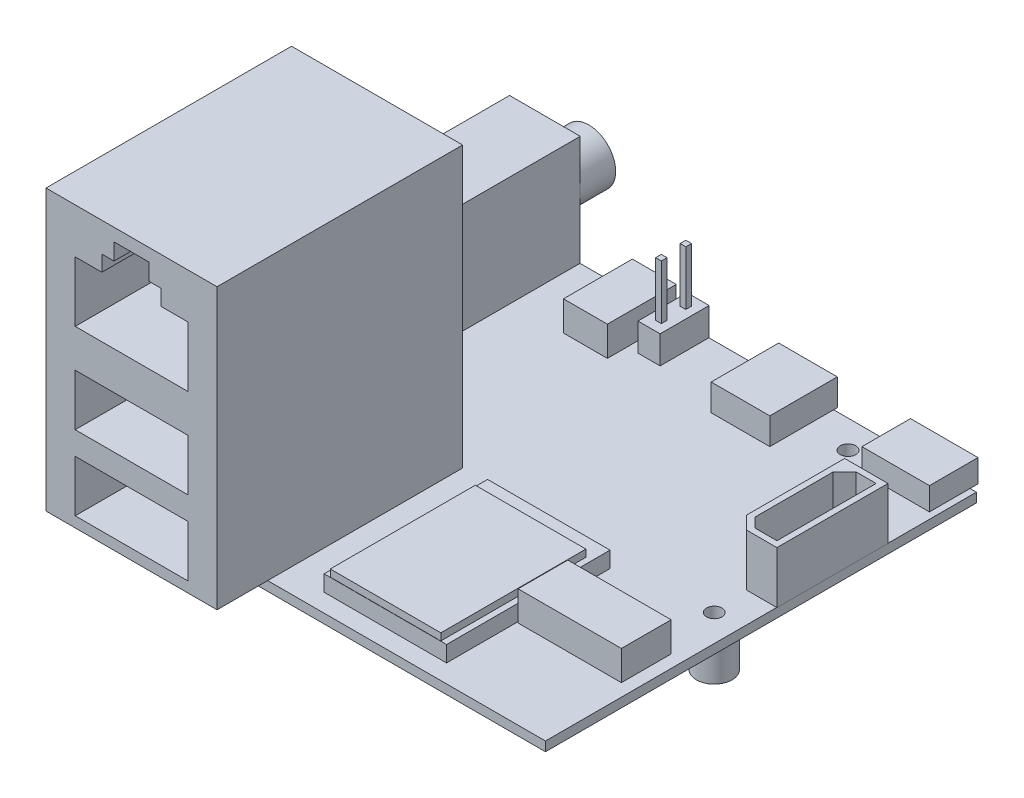
SolidWorks part; units mm, degrees
material "Delrin 2700 NC010, Low Viscosity Acetal Copolymer (SS)"
ref_plane "Front Plane" through (0, 0, 0) normal (0, 0, 1) x (1, 0, 0)
ref_plane "Top Plane" through (0, 0, 0) normal (0, 1, 0) x (1, 0, 0)
ref_plane "Right Plane" through (0, 0, 0) normal (1, 0, 0) x (0, 0, -1)
sketch "Sketch1" plane through (0, 0, 0) normal (0, 1, 0) x (1, 0, 0)
  line L1 (0, 0) -> (52, 0)
  line L2 (0, 0) -> (0, 48)
  line L3 (0, 48) -> (52, 48)
  line L4 (52, 0) -> (52, 48)
  dimension "D1" = 52
  dimension "D2" = 48
extrude "Base" add sketch "Sketch1" along normal blind 1.04
sketch "Sketch3" plane through (0, 1.04, 0) normal (0, 1, 0) x (1, 0, 0)
  line L0 (0, 0) -> (52, 0) construction
  line L1 (21.0566, 21.7112) -> (2.0066, 21.7112)
  line L2 (21.0566, 21.7112) -> (21.0566, -5.6388)
  line L3 (21.0566, -5.6388) -> (2.0066, -5.6388)
  line L4 (2.0066, 21.7112) -> (2.0066, -5.6388)
  line L5 (0, 48) -> (0, 0) construction
  dimension "D1" = 27.35
  dimension "D2" = 19.05
  dimension "D3" = 5.6388
  dimension "D4" = 2.0066
extrude "Ethernet-USB-LinkPP" add sketch "Sketch3" along normal blind 31.1658
sketch "Sketch4" plane through (0, 0, 5.6388) normal (0, 0, 1) x (1, 0, 0)
  line L1 (5.2578, 7.9488) -> (17.8054, 7.9488)
  line L2 (5.2578, 7.9488) -> (5.2578, 2.2084)
  line L3 (5.2578, 2.2084) -> (17.8054, 2.2084)
  line L4 (17.8054, 7.9488) -> (17.8054, 2.2084)
  line L5 (2.0066, 32.2058) -> (2.0066, 1.04) construction
  line L6 (2.0066, 6.305) -> (5.2578, 6.305) construction
  line L7 (2.0066, 32.2058) -> (21.0566, 32.2058) construction
  line L8 (17.8054, 5.7814) -> (21.0566, 5.7814) construction
  line L9 (21.0566, 32.2058) -> (21.0566, 1.04) construction
  line L11 (5.2578, 16.2546) -> (17.8054, 16.2546)
  line L12 (5.2578, 16.2546) -> (5.2578, 10.5142)
  line L13 (5.2578, 10.5142) -> (17.8054, 10.5142)
  line L14 (17.8054, 16.2546) -> (17.8054, 10.5142)
  dimension "D1" = 12.5476
  dimension "D2" = 5.7404
  dimension "D3" = 24.257
  dimension "D4" = 15.9512
extrude "USB ports" cut sketch "Sketch4" against normal blind 8.89
sketch "Sketch5" plane through (0, 0, 5.6388) normal (0, 0, 1) x (1, 0, 0)
  line L0 (5.2578, 27.1893) -> (8.2296, 27.1893)
  line L1 (9.5758, 30.7961) -> (13.4874, 30.7961)
  line L2 (5.2578, 27.1893) -> (5.2578, 20.4837)
  line L3 (5.2578, 20.4837) -> (17.8054, 20.4837)
  line L4 (17.8054, 27.1893) -> (17.8054, 20.4837)
  line L5 (8.2296, 27.1893) -> (8.2296, 28.9419)
  line L6 (8.2296, 28.9419) -> (9.5758, 28.9419)
  line L7 (9.5758, 28.9419) -> (9.5758, 30.7961)
  line L8 (17.8054, 16.2546) -> (5.2578, 16.2546) construction
  line L9 (17.8054, 10.5142) -> (17.8054, 16.2546) construction
  line L10 (2.0066, 32.2058) -> (2.0066, 1.04) construction
  line L11 (11.5316, 30.2362) -> (11.5316, 20.4837) construction
  line L12 (17.8054, 27.1893) -> (14.8336, 27.1893)
  line L13 (14.8336, 27.1893) -> (14.8336, 28.9419)
  line L14 (14.8336, 28.9419) -> (13.4874, 28.9419)
  line L15 (13.4874, 28.9419) -> (13.4874, 30.7961)
  line L16 (2.0066, 32.2058) -> (21.0566, 32.2058) construction
  dimension "D1" = 10.3124
  dimension "D2" = 6.7056
  dimension "D3" = 8.4582
  dimension "D4" = 6.223
  dimension "D5" = 7.5692
  dimension "D6" = 1.4097
extrude "Ethernet port" cut sketch "Sketch5" against normal blind 11.4681
sketch "Sketch6" plane through (0, 1.04, 0) normal (0, 1, 0) x (1, 0, 0)
  line L1 (7.8486, 48.0254) -> (-0.0254, 48.0254)
  line L2 (7.8486, 48.0254) -> (7.8486, 34.0554)
  line L3 (7.8486, 34.0554) -> (-0.0254, 34.0554)
  line L4 (-0.0254, 48.0254) -> (-0.0254, 34.0554)
  line L6 (52, 48) -> (0, 48) construction
  line L7 (0, 48) -> (0, 0) construction
  dimension "D1" = 13.97
  dimension "D2" = 7.874
  dimension "D3" = 0.0254
  dimension "D4" = 0.0254
extrude "Headphone jack" add sketch "Sketch6" along normal blind 12.2428
sketch "Sketch7" plane through (0, 0, -48) normal (0, 0, -1) x (-1, 0, 0)
  line L1 (-4.8514, 4.9135) -> (4.6266, 4.9135) construction
  line L2 (-7.8486, 13.2828) -> (0.0254, 13.2828) construction
  line L3 (-7.8486, 7.9107) -> (-7.8486, 4.1042) construction
  line L4 (0, 1.04) -> (0, 0) construction
  circle A0 centre (-4.8514, 7.9107) radius 2.9972
  circle A1 centre (-4.8514, 7.9107) radius 1.7653
  dimension "D1" = 5.9944
  dimension "D4" = 3.5306
  dimension "D2" = 8.3693
  dimension "D3" = 7.8486
extrude "Headphone jack circle" add sketch "Sketch7" along normal blind 3.9751
sketch "Sketch8" plane through (0, 1.04, 0) normal (0, 1, 0) x (1, 0, 0)
  line L1 (13.6525, 48.0254) -> (18.542, 48.0254)
  line L2 (13.6525, 48.0254) -> (13.6525, 40.3546)
  line L3 (13.6525, 40.3546) -> (18.542, 40.3546)
  line L4 (18.542, 48.0254) -> (18.542, 40.3546)
  line L5 (0, 34.0554) -> (0, 0) construction
  line L7 (52, 48) -> (7.8486, 48) construction
  dimension "D1" = 7.6708
  dimension "D2" = 4.8895
  dimension "D3" = 18.542
  dimension "D4" = 0.0254
extrude "DC power" add sketch "Sketch8" along normal blind 3.302
sketch "Sketch9" plane through (0, 0, -48.0254) normal (0, 0, -1) x (-1, 0, 0)
  line L0 (-17.3472, 2.3154) -> (-18.542, 2.3154) construction
  line L1 (-18.542, 4.342) -> (-18.542, 1.04) construction
  line L2 (-14.8472, 2.3154) -> (-13.6525, 2.3154) construction
  line L3 (-13.6525, 4.342) -> (-13.6525, 1.04) construction
  line L4 (-18.542, 1.0654) -> (-13.6525, 1.0654) construction
  line L5 (-18.542, 1.04) -> (-13.6525, 1.04) construction
  line L6 (-13.6525, 4.342) -> (-13.6525, 1.04) construction
  line L7 (-18.542, 4.342) -> (-18.542, 1.04) construction
  circle A0 centre (-16.0972, 2.3154) radius 1.25
  dimension "D1" = 2.5
  dimension "D2" = 0.0254
extrude "DC power hole" cut sketch "Sketch9" against normal blind 5.842
sketch "Sketch10" plane through (0, 0, -42.1834) normal (0, 0, -1) x (-1, 0, 0)
  circle A0 centre (-16.0972, 2.3154) radius 0.4
  circle A2 centre (-16.0972, 2.3154) radius 1.25 construction
  dimension "D1" = 0.8
extrude "DC power pin" add sketch "Sketch10" along normal blind 4.1656
sketch "Sketch11" plane through (0, 1.04, 0) normal (0, 1, 0) x (1, 0, 0)
  line L0 (52, 48) -> (18.542, 48) construction
  line L1 (22.2058, 42.5644) -> (19.742, 42.5644)
  line L2 (22.2058, 42.5644) -> (22.2058, 48.0254)
  line L3 (22.2058, 48.0254) -> (19.742, 48.0254)
  line L4 (19.742, 42.5644) -> (19.742, 48.0254)
  line L5 (52, 0) -> (52, 48) construction
  dimension "D1" = 0.0254
  dimension "D2" = 2.4638
  dimension "D3" = 5.461
  dimension "D4" = 32.258
extrude "PWM pin base" add sketch "Sketch11" along normal blind 3.0988
sketch "Sketch12" plane through (0, 4.1388, 0) normal (0, 1, 0) x (1, 0, 0)
  line L0 (22.2058, 45.2949) -> (19.742, 45.2949) construction
  line L1 (21.2914, 43.6121) -> (20.6564, 43.6121)
  line L2 (21.2914, 43.6121) -> (21.2914, 44.2471)
  line L3 (21.2914, 44.2471) -> (20.6564, 44.2471)
  line L4 (20.6564, 43.6121) -> (20.6564, 44.2471)
  line L5 (22.2058, 42.5644) -> (22.2058, 48.0254) construction
  line L6 (19.742, 48.0254) -> (19.742, 42.5644) construction
  line L7 (20.9739, 42.5644) -> (20.9739, 48.0254) construction
  line L8 (19.742, 42.5644) -> (22.2058, 42.5644) construction
  line L9 (22.2058, 48.0254) -> (19.742, 48.0254) construction
  line L10 (20.9739, 43.6121) -> (20.9739, 44.2471) construction
  line L11 (21.1837, 42.5644) -> (21.1837, 43.6121) construction
  line L12 (21.2914, 46.9776) -> (21.2914, 46.3426)
  line L13 (21.1837, 44.2471) -> (21.1837, 45.2949) construction
  line L14 (21.2914, 46.3426) -> (20.6564, 46.3426)
  line L15 (21.2914, 46.9776) -> (20.6564, 46.9776)
  line L16 (20.6564, 46.9776) -> (20.6564, 46.3426)
  dimension "D1" = 0.635
  dimension "D2" = 0.635
extrude "PWM pins" add sketch "Sketch12" along normal blind 6.0452
sketch "Sketch13" plane through (0, 1.04, 0) normal (0, 1, 0) x (1, 0, 0)
  line L0 (52, 48) -> (22.2058, 48) construction
  line L1 (36.0996, 40.888) -> (29.5718, 40.888)
  line L2 (36.0996, 40.888) -> (36.0996, 48.4064)
  line L3 (36.0996, 48.4064) -> (29.5718, 48.4064)
  line L4 (29.5718, 40.888) -> (29.5718, 48.4064)
  line L5 (52, 0) -> (52, 48) construction
  dimension "D1" = 6.5278
  dimension "D2" = 0.4064
  dimension "D3" = 7.5184
  dimension "D4" = 22.4282
extrude "Micro HDMI port" add sketch "Sketch13" along normal blind 2.9718
sketch "Sketch14" plane through (0, 1.04, 0) normal (0, 1, 0) x (1, 0, 0)
  line L0 (52, 48) -> (36.0996, 48) construction
  line L1 (51.2888, 43.4788) -> (43.7704, 43.4788)
  line L2 (51.2888, 43.4788) -> (51.2888, 48.889)
  line L3 (51.2888, 48.889) -> (43.7704, 48.889)
  line L4 (43.7704, 43.4788) -> (43.7704, 48.889)
  line L5 (52, 0) -> (52, 48) construction
  dimension "D1" = 7.5184
  dimension "D2" = 5.4102
  dimension "D3" = 0.889
  dimension "D4" = 8.2296
extrude "Micro USB port" add sketch "Sketch14" along normal blind 2.54
sketch "Sketch15" plane through (0, 0, 0) normal (0, -1, 0) x (-1, 0, 0)
  line L0 (0, 0) -> (-52, 0) construction
  line L1 (0, 48) -> (0, 0) construction
  line L2 (-40.8, 45.7648) -> (-44.7677, 45.7648) construction
  line L3 (-52, 48) -> (0, 48) construction
  circle A0 centre (-3, 30.1) radius 0.8636
  circle A1 centre (-49, 21.8012) radius 0.8636
  circle A2 centre (-40.8, 44.9012) radius 0.8636
  dimension "D1" = 30.1
  dimension "D2" = 3
  dimension "D3" = 1.7272
  dimension "D5" = 37.8
  dimension "D6" = 23.1
  dimension "D7" = 2.2352
  dimension "D4" = 49
extrude "Header hole" cut sketch "Sketch15" against normal up to next
sketch "Sketch16" plane through (0, 0, 0) normal (0, -1, 0) x (1, 0, 0)
  circle A0 centre (49, -21.8012) radius 1.9939
  circle A2 centre (3, -30.1) radius 1.9939
  circle A3 centre (49, -21.8012) radius 0.8636 construction
  circle A5 centre (3, -30.1) radius 0.8636 construction
  dimension "D1" = 3.9878
extrude "Standoffs 1" add sketch "Sketch16" along normal blind 4.4704
sketch "Sketch17" plane through (0, 0, 0) normal (0, -1, 0) x (1, 0, 0)
  circle A0 centre (40.8, -44.9012) radius 1.9939
  circle A1 centre (40.8, -44.9012) radius 0.8636 construction
  circle A2 centre (49, -21.8012) radius 1.9939 construction
extrude "Short standoff" add sketch "Sketch17" along normal blind 1.9939
sketch "Sketch19" plane through (0, 0, 0) normal (0, -1, 0) x (1, 0, 0)
  circle A1 centre (40.8, -44.9012) radius 0.8636
  circle A2 centre (40.8, -44.9012) radius 0.8636
  circle A3 centre (49, -21.8012) radius 0.8636
  circle A4 centre (49, -21.8012) radius 0.8636
  circle A5 centre (3, -30.1) radius 0.8636
  circle A6 centre (3, -30.1) radius 0.8636
  dimension "D1" = 0
  dimension "D2" = 0
  dimension "D3" = 0
extrude "Threads in standoffs" cut sketch "Sketch19" along normal up to next
sketch "Sketch20" plane through (0, 0, 0) normal (0, -1, 0) x (-1, 0, 0)
  line L0 (-52, 0) -> (-52, 48) construction
  line L1 (-43.872, 25.14) -> (-31.7562, 25.14)
  line L2 (-43.872, 25.14) -> (-43.872, 37.2558)
  line L3 (-43.872, 37.2558) -> (-31.7562, 37.2558)
  line L4 (-31.7562, 25.14) -> (-31.7562, 37.2558)
  line L5 (-52, 48) -> (0, 48) construction
  dimension "D1" = 12.1158
  dimension "D2" = 12.1158
  dimension "D3" = 20.2438
  dimension "D4" = 22.86
extrude "CPU" add sketch "Sketch20" along normal blind 1.4732
sketch "Sketch21" plane through (0, 1.04, 0) normal (0, 1, 0) x (1, 0, 0)
  line L0 (52, 0) -> (52, 48) construction
  line L1 (52.0254, 38.1254) -> (47.1994, 38.1254)
  line L2 (52.0254, 38.1254) -> (52.0254, 25.7556)
  line L3 (52.0254, 25.7556) -> (48.6362, 25.7556)
  line L4 (47.1994, 38.1254) -> (47.1994, 27.1924)
  line L5 (21.0566, 0) -> (52, 0) construction
  line L6 (47.1994, 27.1924) -> (48.6362, 25.7556)
  dimension "D1" = 0.0254
  dimension "D2" = 12.3698
  dimension "D3" = 4.826
  dimension "D4" = 38.1254
  dimension "D5" = 2.032
  dimension "D6" = 45
extrude "UART plastic" add sketch "Sketch21" along normal blind 5.7912
sketch "Sketch22" plane through (0, 6.8312, 0) normal (0, 1, 0) x (1, 0, 0)
  line L0 (51.365, 37.465) -> (49.135, 37.465)
  line L1 (47.8598, 36.1898) -> (47.8598, 27.466)
  line L2 (47.8598, 27.466) -> (48.9098, 26.416)
  line L3 (48.9098, 26.416) -> (51.365, 26.416)
  line L4 (51.365, 26.416) -> (51.365, 37.465)
  line L5 (52.0254, 38.1254) -> (47.1994, 38.1254)
  line L6 (47.1994, 38.1254) -> (47.1994, 27.1924)
  line L7 (47.1994, 27.1924) -> (48.6362, 25.7556)
  line L8 (48.6362, 25.7556) -> (52.0254, 25.7556)
  line L9 (52.0254, 25.7556) -> (52.0254, 38.1254)
  line L10 (52.0254, 38.1254) -> (47.1994, 38.1254) construction
  line L11 (47.1994, 38.1254) -> (47.1994, 27.1924) construction
  line L12 (47.1994, 27.1924) -> (48.6362, 25.7556) construction
  line L13 (48.6362, 25.7556) -> (52.0254, 25.7556) construction
  line L14 (52.0254, 25.7556) -> (52.0254, 38.1254) construction
  line L15 (47.8598, 36.1898) -> (49.135, 37.465)
  line L17 (51.365, 37.465) -> (47.8598, 37.465) construction
  line L18 (47.8598, 37.465) -> (47.8598, 27.466) construction
  dimension "D3" = 45
  dimension "D4" = 1.8034
  dimension "D1" = 0
  dimension "D2" = 0.6604
extrude "UART hole" cut sketch "Sketch22" against normal blind 4.1656
sketch "Sketch23" plane through (0, 1.04, 0) normal (0, 1, 0) x (1, 0, 0)
  line L0 (52, 0) -> (52, 25.7556) construction
  line L1 (39.0968, 15.3924) -> (50.603, 15.3924)
  line L2 (39.0968, 15.3924) -> (39.0968, 9.8552)
  line L3 (39.0968, 9.8552) -> (50.603, 9.8552)
  line L4 (50.603, 15.3924) -> (50.603, 9.8552)
  line L5 (21.0566, 0) -> (52, 0) construction
  dimension "D1" = 11.5062
  dimension "D2" = 5.5372
  dimension "D3" = 12.9032
  dimension "D4" = 15.3924
extrude "MicroSD" add sketch "Sketch23" along normal blind 3.302
sketch "Sketch24" plane through (0, 1.04, 0) normal (0, 1, 0) x (1, 0, 0)
  line L0 (21.0566, 0) -> (52, 0) construction
  line L1 (25.3238, 20.2311) -> (38.9636, 20.2311)
  line L2 (25.3238, 20.2311) -> (25.3238, 2.0193)
  line L3 (25.3238, 2.0193) -> (38.9636, 2.0193)
  line L4 (38.9636, 20.2311) -> (38.9636, 2.0193)
  line L6 (21.0566, 0) -> (21.0566, 21.7112) construction
  dimension "D1" = 18.2118
  dimension "D2" = 13.6398
  dimension "D3" = 20.2311
  dimension "D4" = 4.2672
extrude "eMMC board" add sketch "Sketch24" along normal blind 1.778
sketch "Sketch25" plane through (0, 2.818, 0) normal (0, 1, 0) x (1, 0, 0)
  line L0 (25.3238, 2.0193) -> (38.9636, 2.0193) construction
  line L1 (25.9842, 18.1991) -> (38.3032, 18.1991)
  line L2 (25.9842, 18.1991) -> (25.9842, 2.0447)
  line L3 (25.9842, 2.0447) -> (38.3032, 2.0447)
  line L4 (38.3032, 18.1991) -> (38.3032, 2.0447)
  line L5 (38.9636, 2.0193) -> (38.9636, 20.2311) construction
  line L6 (25.3238, 15.3001) -> (25.9842, 15.3001) construction
  line L7 (25.3238, 20.2311) -> (25.3238, 2.0193) construction
  line L9 (38.3032, 15.3001) -> (38.9636, 15.3001) construction
  dimension "D1" = 0.0254
  dimension "D2" = 16.1544
  dimension "D3" = 12.9794
extrude "eMMC chip" add sketch "Sketch25" along normal blind 0.7874
